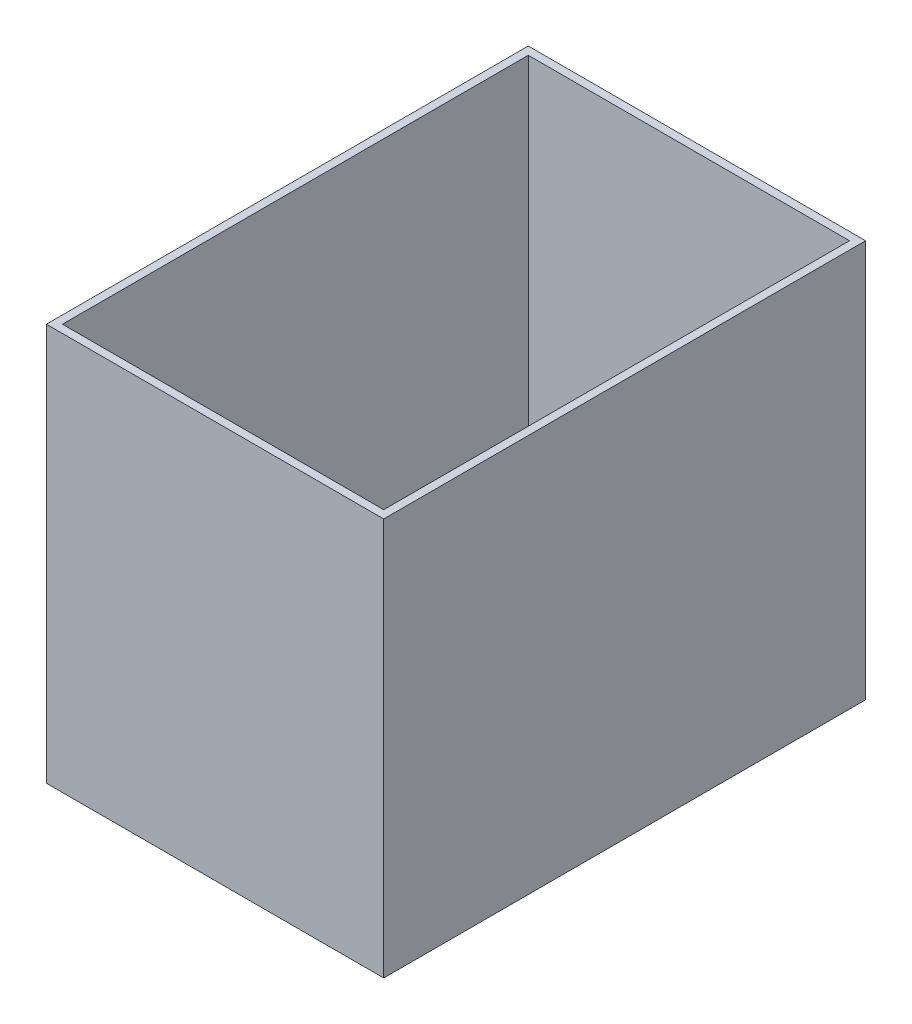
SolidWorks part; units mm, degrees
ref_plane "前视基准面" through (0, 0, 0) normal (0, 0, 1) x (1, 0, 0)
ref_plane "上视基准面" through (0, 0, 0) normal (0, 1, 0) x (1, 0, 0)
ref_plane "右视基准面" through (0, 0, 0) normal (1, 0, 0) x (0, 0, -1)
other "Configuration Table"
sketch "草图1" plane through (0, 0, 0) normal (0, 1, 0) x (1, 0, 0)
  line L1 (100, -145) -> (-100, -145)
  line L2 (100, -145) -> (100, 145)
  line L3 (100, 145) -> (-100, 145)
  line L4 (-100, -145) -> (-100, 145)
  line L5 (100, -145) -> (-100, 145) construction
  line L6 (100, 145) -> (-100, -145) construction
  line L7 (-105, 150) -> (105, 150)
  line L8 (-105, 150) -> (-105, -150)
  line L9 (-105, -150) -> (105, -150)
  line L10 (105, 150) -> (105, -150)
  line L11 (-105, 150) -> (105, -150) construction
  line L12 (-105, -150) -> (105, 150) construction
  point P0 (0, 0)
  point P6 (0, 0)
  dimension "D1" = 300
  dimension "D2" = 210
  dimension "D3" = 290
  dimension "D4" = 200
extrude "凸台-拉伸1" add sketch "草图1" along normal blind 247.5
